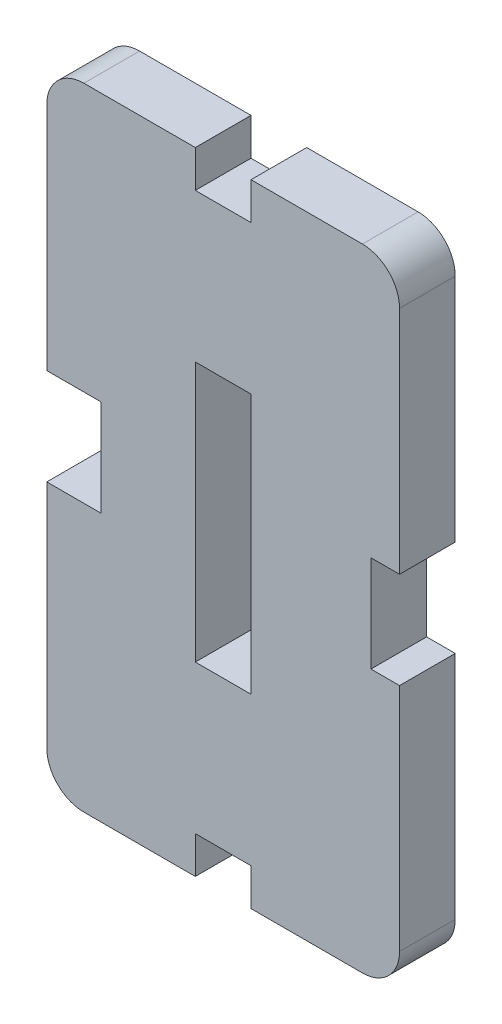
SolidWorks part; units mm, degrees
ref_plane "Front" through (0, 0, 0) normal (0, 0, 1) x (1, 0, 0)
ref_plane "Top" through (0, 0, 0) normal (0, 1, 0) x (1, 0, 0)
ref_plane "Right" through (0, 0, 0) normal (1, 0, 0) x (0, 0, -1)
sketch "Sketch1" plane through (0, 0, 0) normal (0, 0, 1) x (1, 0, 0)
  line L0 (-1044.1169, 45.9977) -> (-1044.1169, 31.9977)
  line L1 (-1049.1904, 38.9977) -> (-1034.6577, 38.9977) construction
  line L2 (-1041.1169, 31.9977) -> (-1041.1169, 45.9977)
  line L3 (-1041.1169, 45.9977) -> (-1044.1169, 45.9977)
  line L4 (-1033.1169, 53.9977) -> (-1033.1169, 41.5931)
  line L5 (-1033.1169, 41.5931) -> (-1034.6577, 41.5931)
  line L6 (-1034.6577, 41.5931) -> (-1034.6577, 36.4024)
  line L7 (-1050.1169, 21.9977) -> (-1044.1169, 21.9977)
  line L8 (-1042.6169, 53.9977) -> (-1041.1169, 53.9977)
  line L9 (-1041.1169, 53.9977) -> (-1041.1169, 55.9977)
  line L10 (-1041.1169, 55.9977) -> (-1035.1169, 55.9977)
  line L11 (-1042.6169, 53.9977) -> (-1044.1169, 53.9977)
  line L12 (-1044.1169, 53.9977) -> (-1044.1169, 55.9977)
  line L13 (-1052.1169, 36.4024) -> (-1052.1169, 23.9977)
  line L14 (-1049.1904, 36.4024) -> (-1052.1169, 36.4024)
  line L15 (-1044.1169, 23.9977) -> (-1044.1169, 21.9977)
  line L16 (-1042.6169, 23.9977) -> (-1044.1169, 23.9977)
  line L17 (-1041.1169, 21.9977) -> (-1035.1169, 21.9977)
  line L18 (-1049.1904, 36.4024) -> (-1049.1904, 41.5931)
  line L19 (-1049.1904, 41.5931) -> (-1052.1169, 41.5931)
  line L20 (-1052.1169, 41.5931) -> (-1052.1169, 53.9977)
  line L21 (-1041.1169, 23.9977) -> (-1041.1169, 21.9977)
  line L22 (-1042.6169, 23.9977) -> (-1041.1169, 23.9977)
  line L23 (-1033.1169, 36.4024) -> (-1034.6577, 36.4024)
  line L24 (-1050.1169, 55.9977) -> (-1044.1169, 55.9977)
  line L25 (-1033.1169, 23.9977) -> (-1033.1169, 36.4024)
  line L26 (-1041.1169, 31.9977) -> (-1044.1169, 31.9977)
  arc A0 (-1052.1169, 53.9977) -> (-1050.1169, 55.9977) centre (-1050.1169, 53.9977) cw
  arc A1 (-1033.1169, 53.9977) -> (-1035.1169, 55.9977) centre (-1035.1169, 53.9977) ccw
  arc A2 (-1033.1169, 23.9977) -> (-1035.1169, 21.9977) centre (-1035.1169, 23.9977) cw
  arc A3 (-1052.1169, 23.9977) -> (-1050.1169, 21.9977) centre (-1050.1169, 23.9977) ccw
  point P8 (-1044.1169, 38.9977)
  point P38 (-1041.1169, 38.9977)
  dimension "D1" = 2
  dimension "D2" = 3
  dimension "D3" = 8
  dimension "D4" = 8
  dimension "D5" = 14
  dimension "D6" = 2
  dimension "D7" = 34
extrude "Base-Extrude" add sketch "Sketch1" along normal blind 3
